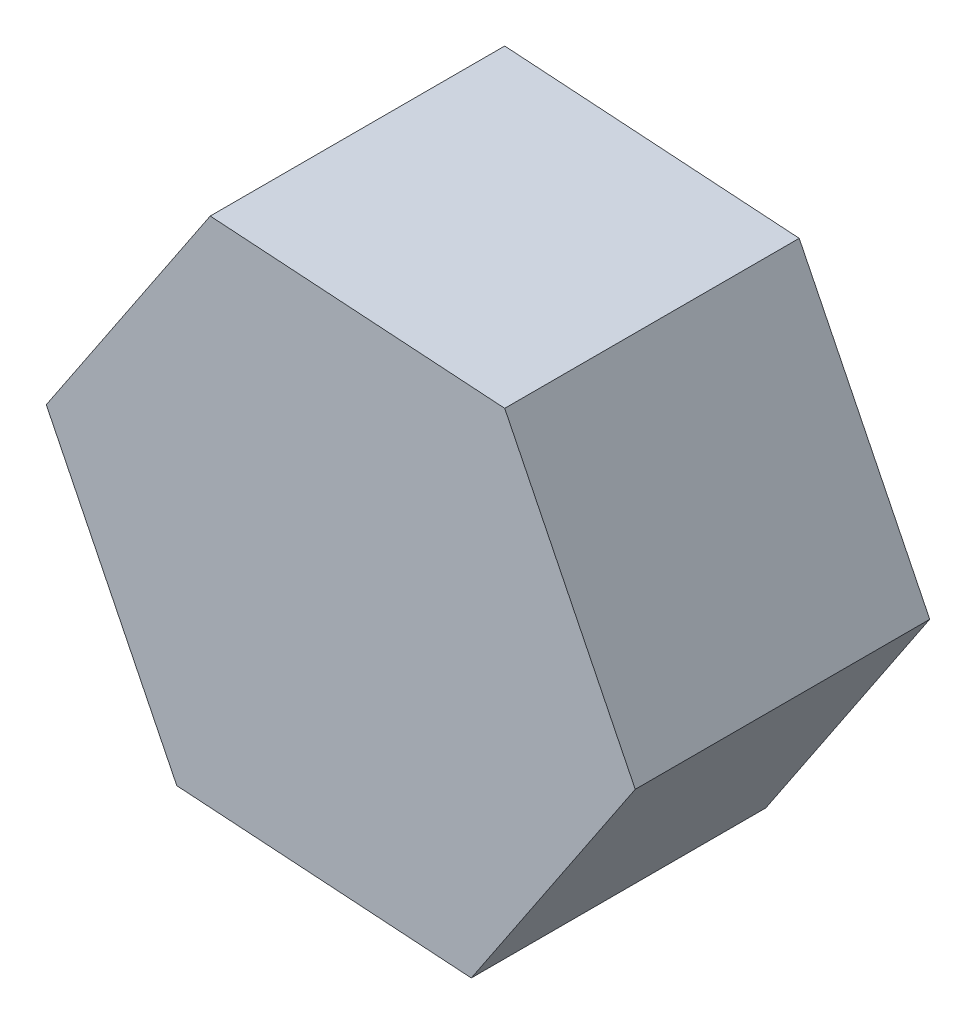
SolidWorks part; units mm, degrees
ref_plane "Front Plane" through (0, 0, 0) normal (0, 0, 1) x (1, 0, 0)
ref_plane "Top Plane" through (0, 0, 0) normal (0, 1, 0) x (1, 0, 0)
ref_plane "Right Plane" through (0, 0, 0) normal (1, 0, 0) x (0, 0, -1)
sketch "Sketch1" plane through (0, 0, 0) normal (0, 0, 1) x (1, 0, 0)
  line L1 (6.6812, 9.999) -> (-5.3188, 10.7856)
  line L2 (-5.3188, 10.7856) -> (-12, 0.7865)
  line L3 (-12, 0.7865) -> (-6.6812, -9.999)
  line L4 (-6.6812, -9.999) -> (5.3188, -10.7856)
  line L5 (5.3188, -10.7856) -> (12, -0.7865)
  line L6 (12, -0.7865) -> (6.6812, 9.999)
  circle A0 centre (0, 0) radius 10.4146 construction
  dimension "D1" = 24
extrude "Boss-Extrude1" add sketch "Sketch1" along normal blind 12
sketch "Sketch6" plane through (0, 0, 0) normal (0, 1, 0) x (1, 0, 0)
  line L3 (0, -4.1242) -> (0, 1.3709) construction
  line L7 (12, 0) -> (6.6812, 0) construction
